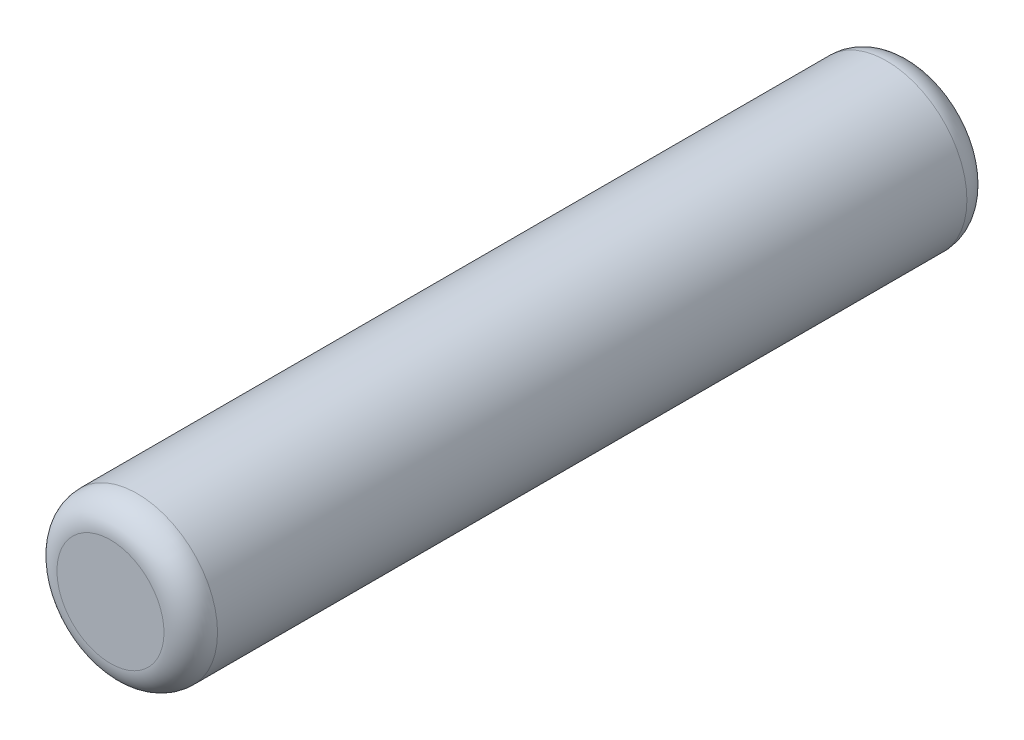
SolidWorks part; units mm, degrees
ref_plane "Płaszczyzna przednia" through (0, 0, 0) normal (0, 0, 1) x (1, 0, 0)
ref_plane "Płaszczyzna górna" through (0, 0, 0) normal (0, 1, 0) x (1, 0, 0)
ref_plane "Płaszczyzna prawa" through (0, 0, 0) normal (1, 0, 0) x (0, 0, -1)
sketch "Szkic1" plane through (0, 0, 0) normal (0, 0, 1) x (1, 0, 0)
  circle A0 centre (0, 0) radius 0.6
  dimension "D1" = 1.2
extrude "Dodanie-wyciągnięcie1" add sketch "Szkic1" along normal mid plane 6
fillet "Zaokrąglenie1" radius 0.2 2 edges at (0.6, 0, -3) (0.6, 0, 3)
